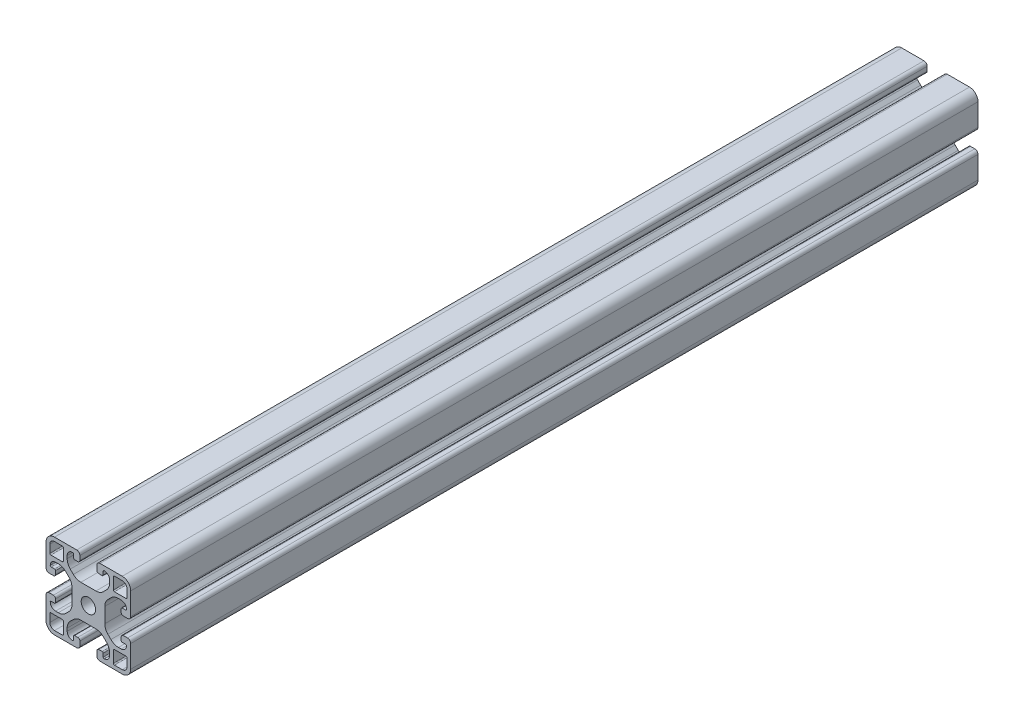
SolidWorks part; units mm, degrees
ref_plane "Plan de face" through (0, 0, 0) normal (0, 0, 1) x (1, 0, 0)
ref_plane "Plan de dessus" through (0, 0, 0) normal (0, 1, 0) x (1, 0, 0)
ref_plane "Plan de droite" through (0, 0, 0) normal (1, 0, 0) x (0, 0, -1)
ref_plane "Plan1" through (0, 0, -30) normal (0, 0, -1) x (-1, 0, 0)
sketch "Esquisse1" plane through (0, 0, -30) normal (0, 0, -1) x (-1, 0, 0)
  line L0 (-4.5, 15) -> (-4.5, 13.5)
  line L1 (-4, 13) -> (-2.5, 13)
  line L2 (-4.5, 10) -> (-5.8076, 10)
  line L3 (-9.3431, 11.4645) -> (-10.7855, 12.9069)
  line L4 (-12.25, 16.4424) -> (-12.25, 23.5576)
  line L5 (-10.7855, 27.0931) -> (-9.3431, 28.5355)
  line L6 (-5.8076, 30) -> (-4.5, 30)
  line L7 (-2.5, 27) -> (-4, 27)
  line L8 (-4.5, 26.5) -> (-4.5, 25)
  line L9 (-3.5, 24) -> (-1.5, 24)
  line L10 (0, 25.5) -> (0, 36)
  line L11 (-4, 40) -> (-14.5, 40)
  line L12 (-16, 38.5) -> (-16, 36.5)
  line L13 (-15, 35.5) -> (-13.5, 35.5)
  line L14 (-13, 36) -> (-13, 37.5)
  line L15 (-10, 35.5) -> (-10, 34.1924)
  line L16 (-11.4645, 30.6569) -> (-12.9069, 29.2145)
  line L17 (-16.4424, 27.75) -> (-23.5576, 27.75)
  line L18 (-27.0931, 29.2145) -> (-28.5355, 30.6569)
  line L19 (-30, 34.1924) -> (-30, 35.5)
  line L20 (-27, 37.5) -> (-27, 36)
  line L21 (-26.5, 35.5) -> (-25, 35.5)
  line L22 (-24, 36.5) -> (-24, 38.5)
  line L23 (-25.5, 40) -> (-36, 40)
  line L24 (-40, 36) -> (-40, 25.5)
  line L25 (-38.5, 24) -> (-36.5, 24)
  line L26 (-35.5, 25) -> (-35.5, 26.5)
  line L27 (-36, 27) -> (-37.5, 27)
  line L28 (-35.5, 30) -> (-34.1924, 30)
  line L29 (-30.6569, 28.5355) -> (-29.2145, 27.0931)
  line L30 (-27.75, 23.5576) -> (-27.75, 16.4424)
  line L31 (-29.2145, 12.9069) -> (-30.6569, 11.4645)
  line L32 (-34.1924, 10) -> (-35.5, 10)
  line L33 (-37.5, 13) -> (-36, 13)
  line L34 (-35.5, 13.5) -> (-35.5, 15)
  line L35 (-36.5, 16) -> (-38.5, 16)
  line L36 (-40, 14.5) -> (-40, 4)
  line L37 (-36, 0) -> (-25.5, 0)
  line L38 (-24, 1.5) -> (-24, 3.5)
  line L39 (-25, 4.5) -> (-26.5, 4.5)
  line L40 (-27, 4) -> (-27, 2.5)
  line L41 (-30, 4.5) -> (-30, 5.8076)
  line L42 (-28.5355, 9.3431) -> (-27.0931, 10.7855)
  line L43 (-23.5576, 12.25) -> (-16.4424, 12.25)
  line L44 (-12.9069, 10.7855) -> (-11.4645, 9.3431)
  line L45 (-10, 5.8076) -> (-10, 4.5)
  line L46 (-13, 2.5) -> (-13, 4)
  line L47 (-13.5, 4.5) -> (-15, 4.5)
  line L48 (-16, 3.5) -> (-16, 1.5)
  line L49 (-14.5, 0) -> (-4, 0)
  line L50 (0, 4) -> (0, 14.5)
  line L51 (-1.5, 16) -> (-3.5, 16)
  line L52 (-4, 1.8) -> (-7.7, 1.8)
  line L53 (-8.2, 2.3) -> (-8.2, 7.7)
  line L54 (-7.7, 8.2) -> (-2.3, 8.2)
  line L55 (-1.8, 7.7) -> (-1.8, 4)
  line L56 (-38.2, 4) -> (-38.2, 7.7)
  line L57 (-37.7, 8.2) -> (-32.3, 8.2)
  line L58 (-31.8, 7.7) -> (-31.8, 2.3)
  line L59 (-32.3, 1.8) -> (-36, 1.8)
  line L60 (-36, 38.2) -> (-32.3, 38.2)
  line L61 (-31.8, 37.7) -> (-31.8, 32.3)
  line L62 (-32.3, 31.8) -> (-37.7, 31.8)
  line L63 (-38.2, 32.3) -> (-38.2, 36)
  line L64 (-1.8, 36) -> (-1.8, 32.3)
  line L65 (-2.3, 31.8) -> (-7.7, 31.8)
  line L66 (-8.2, 32.3) -> (-8.2, 37.7)
  line L67 (-7.7, 38.2) -> (-4, 38.2)
  arc A0 (-4.5, 13.5) -> (-4, 13) centre (-4, 13.5) ccw
  arc A1 (-2.5, 13) -> (-2, 12.5) centre (-2.5, 12.5) cw
  arc A2 (-2, 12.5) -> (-4.5, 10) centre (-4.5, 12.5) cw
  arc A3 (-5.8076, 10) -> (-9.3431, 11.4645) centre (-5.8076, 15) cw
  arc A4 (-10.7855, 12.9069) -> (-12.25, 16.4424) centre (-7.25, 16.4424) cw
  arc A5 (-12.25, 23.5576) -> (-10.7855, 27.0931) centre (-7.25, 23.5576) cw
  arc A6 (-9.3431, 28.5355) -> (-5.8076, 30) centre (-5.8076, 25) cw
  arc A7 (-4.5, 30) -> (-2, 27.5) centre (-4.5, 27.5) cw
  arc A8 (-2, 27.5) -> (-2.5, 27) centre (-2.5, 27.5) cw
  arc A9 (-4, 27) -> (-4.5, 26.5) centre (-4, 26.5) ccw
  arc A10 (-4.5, 25) -> (-3.5, 24) centre (-3.5, 25) ccw
  arc A11 (-1.5, 24) -> (0, 25.5) centre (-1.5, 25.5) ccw
  arc A12 (0, 36) -> (-4, 40) centre (-4, 36) ccw
  arc A13 (-14.5, 40) -> (-16, 38.5) centre (-14.5, 38.5) ccw
  arc A14 (-16, 36.5) -> (-15, 35.5) centre (-15, 36.5) ccw
  arc A15 (-13.5, 35.5) -> (-13, 36) centre (-13.5, 36) ccw
  arc A16 (-13, 37.5) -> (-12.5, 38) centre (-12.5, 37.5) cw
  arc A17 (-12.5, 38) -> (-10, 35.5) centre (-12.5, 35.5) cw
  arc A18 (-10, 34.1924) -> (-11.4645, 30.6569) centre (-15, 34.1924) cw
  arc A19 (-12.9069, 29.2145) -> (-16.4424, 27.75) centre (-16.4424, 32.75) cw
  arc A20 (-23.5576, 27.75) -> (-27.0931, 29.2145) centre (-23.5576, 32.75) cw
  arc A21 (-28.5355, 30.6569) -> (-30, 34.1924) centre (-25, 34.1924) cw
  arc A22 (-30, 35.5) -> (-27.5, 38) centre (-27.5, 35.5) cw
  arc A23 (-27.5, 38) -> (-27, 37.5) centre (-27.5, 37.5) cw
  arc A24 (-27, 36) -> (-26.5, 35.5) centre (-26.5, 36) ccw
  arc A25 (-25, 35.5) -> (-24, 36.5) centre (-25, 36.5) ccw
  arc A26 (-24, 38.5) -> (-25.5, 40) centre (-25.5, 38.5) ccw
  arc A27 (-36, 40) -> (-40, 36) centre (-36, 36) ccw
  arc A28 (-40, 25.5) -> (-38.5, 24) centre (-38.5, 25.5) ccw
  arc A29 (-36.5, 24) -> (-35.5, 25) centre (-36.5, 25) ccw
  arc A30 (-35.5, 26.5) -> (-36, 27) centre (-36, 26.5) ccw
  arc A31 (-37.5, 27) -> (-38, 27.5) centre (-37.5, 27.5) cw
  arc A32 (-38, 27.5) -> (-35.5, 30) centre (-35.5, 27.5) cw
  arc A33 (-34.1924, 30) -> (-30.6569, 28.5355) centre (-34.1924, 25) cw
  arc A34 (-29.2145, 27.0931) -> (-27.75, 23.5576) centre (-32.75, 23.5576) cw
  arc A35 (-27.75, 16.4424) -> (-29.2145, 12.9069) centre (-32.75, 16.4424) cw
  arc A36 (-30.6569, 11.4645) -> (-34.1924, 10) centre (-34.1924, 15) cw
  arc A37 (-35.5, 10) -> (-38, 12.5) centre (-35.5, 12.5) cw
  arc A38 (-38, 12.5) -> (-37.5, 13) centre (-37.5, 12.5) cw
  arc A39 (-36, 13) -> (-35.5, 13.5) centre (-36, 13.5) ccw
  arc A40 (-35.5, 15) -> (-36.5, 16) centre (-36.5, 15) ccw
  arc A41 (-38.5, 16) -> (-40, 14.5) centre (-38.5, 14.5) ccw
  arc A42 (-40, 4) -> (-36, 0) centre (-36, 4) ccw
  arc A43 (-25.5, 0) -> (-24, 1.5) centre (-25.5, 1.5) ccw
  arc A44 (-24, 3.5) -> (-25, 4.5) centre (-25, 3.5) ccw
  arc A45 (-26.5, 4.5) -> (-27, 4) centre (-26.5, 4) ccw
  arc A46 (-27, 2.5) -> (-27.5, 2) centre (-27.5, 2.5) cw
  arc A47 (-27.5, 2) -> (-30, 4.5) centre (-27.5, 4.5) cw
  arc A48 (-30, 5.8076) -> (-28.5355, 9.3431) centre (-25, 5.8076) cw
  arc A49 (-27.0931, 10.7855) -> (-23.5576, 12.25) centre (-23.5576, 7.25) cw
  arc A50 (-16.4424, 12.25) -> (-12.9069, 10.7855) centre (-16.4424, 7.25) cw
  arc A51 (-11.4645, 9.3431) -> (-10, 5.8076) centre (-15, 5.8076) cw
  arc A52 (-10, 4.5) -> (-12.5, 2) centre (-12.5, 4.5) cw
  arc A53 (-12.5, 2) -> (-13, 2.5) centre (-12.5, 2.5) cw
  arc A54 (-13, 4) -> (-13.5, 4.5) centre (-13.5, 4) ccw
  arc A55 (-15, 4.5) -> (-16, 3.5) centre (-15, 3.5) ccw
  arc A56 (-16, 1.5) -> (-14.5, 0) centre (-14.5, 1.5) ccw
  arc A57 (-4, 0) -> (0, 4) centre (-4, 4) ccw
  arc A58 (0, 14.5) -> (-1.5, 16) centre (-1.5, 14.5) ccw
  arc A59 (-3.5, 16) -> (-4.5, 15) centre (-3.5, 15) ccw
  circle A60 centre (-20, 20) radius 3.4
  arc A61 (-1.8, 4) -> (-4, 1.8) centre (-4, 4) cw
  arc A62 (-7.7, 1.8) -> (-8.2, 2.3) centre (-7.7, 2.3) cw
  arc A63 (-8.2, 7.7) -> (-7.7, 8.2) centre (-7.7, 7.7) cw
  arc A64 (-2.3, 8.2) -> (-1.8, 7.7) centre (-2.3, 7.7) cw
  arc A65 (-36, 1.8) -> (-38.2, 4) centre (-36, 4) cw
  arc A66 (-38.2, 7.7) -> (-37.7, 8.2) centre (-37.7, 7.7) cw
  arc A67 (-32.3, 8.2) -> (-31.8, 7.7) centre (-32.3, 7.7) cw
  arc A68 (-31.8, 2.3) -> (-32.3, 1.8) centre (-32.3, 2.3) cw
  arc A69 (-38.2, 36) -> (-36, 38.2) centre (-36, 36) cw
  arc A70 (-32.3, 38.2) -> (-31.8, 37.7) centre (-32.3, 37.7) cw
  arc A71 (-31.8, 32.3) -> (-32.3, 31.8) centre (-32.3, 32.3) cw
  arc A72 (-37.7, 31.8) -> (-38.2, 32.3) centre (-37.7, 32.3) cw
  arc A73 (-4, 38.2) -> (-1.8, 36) centre (-4, 36) cw
  arc A74 (-1.8, 32.3) -> (-2.3, 31.8) centre (-2.3, 32.3) cw
  arc A75 (-7.7, 31.8) -> (-8.2, 32.3) centre (-7.7, 32.3) cw
  arc A76 (-8.2, 37.7) -> (-7.7, 38.2) centre (-7.7, 37.7) cw
extrude "Boss.-Extru.1" add sketch "Esquisse1" against normal blind 400
